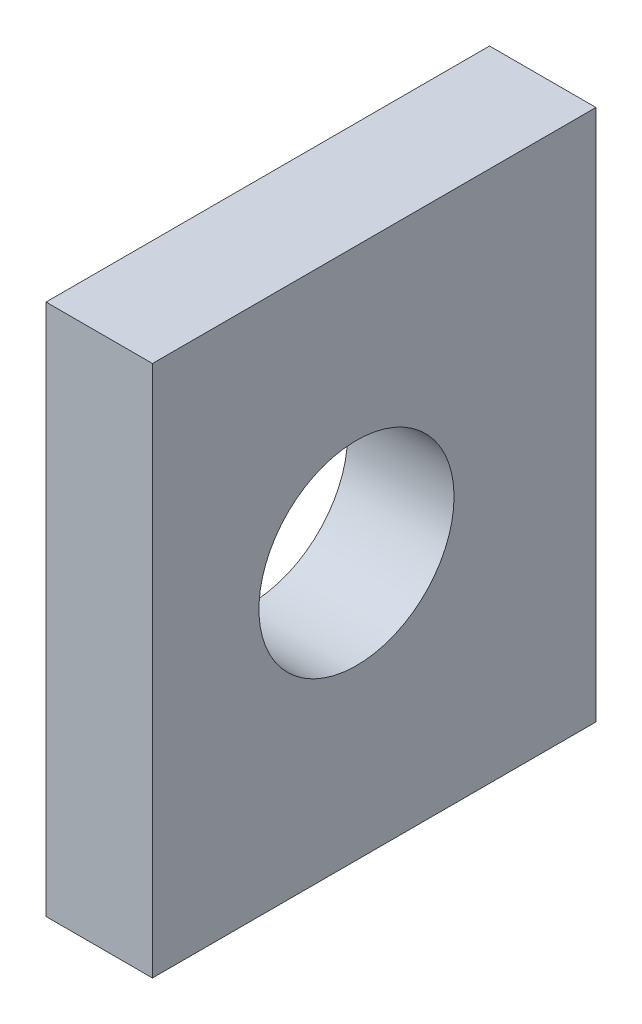
SolidWorks part; units mm, degrees
ref_plane "Front Plane" through (0, 0, 0) normal (0, 0, 1) x (1, 0, 0)
ref_plane "Top Plane" through (0, 0, 0) normal (0, 1, 0) x (1, 0, 0)
ref_plane "Right Plane" through (0, 0, 0) normal (1, 0, 0) x (0, 0, -1)
ref_plane "Plane1" through (513, 0, 0) normal (1, 0, 0) x (0, 0, -1)
sketch "Sketch1" plane through (513, 0, 0) normal (1, 0, 0) x (0, 0, -1)
  line L1 (-130, 270) -> (-180, 270)
  line L2 (-130, 270) -> (-130, 330)
  line L3 (-130, 330) -> (-180, 330)
  line L4 (-180, 270) -> (-180, 330)
extrude "Boss-Extrude1" add sketch "Sketch1" along normal blind 12
sketch "Sketch2" plane through (525, 0, 0) normal (1, 0, 0) x (0, 0, -1)
  circle A0 centre (-157, 300) radius 11
extrude "Cut-Extrude1" cut sketch "Sketch2" against normal blind 32
